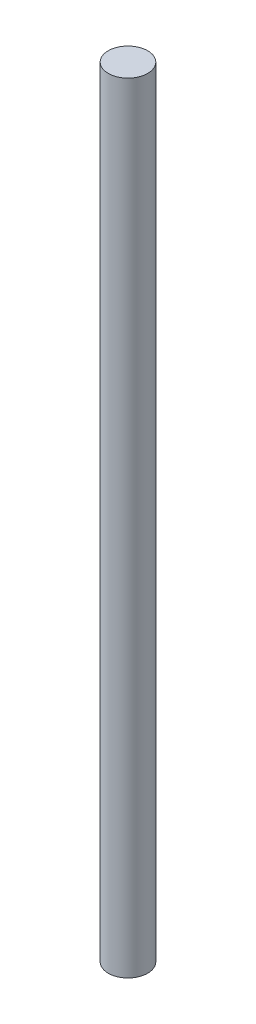
SolidWorks part; units mm, degrees
ref_plane "Front Plane" through (0, 0, 0) normal (0, 0, 1) x (1, 0, 0)
ref_plane "Top Plane" through (0, 0, 0) normal (0, 1, 0) x (1, 0, 0)
ref_plane "Right Plane" through (0, 0, 0) normal (1, 0, 0) x (0, 0, -1)
sketch "Sketch1" plane through (0, 0, 0) normal (0, 1, 0) x (1, 0, 0)
  circle A0 centre (0, 0) radius 1.25
  dimension "D1" = 2.5
extrude "Boss-Extrude1" add sketch "Sketch1" along normal mid plane 49.5
